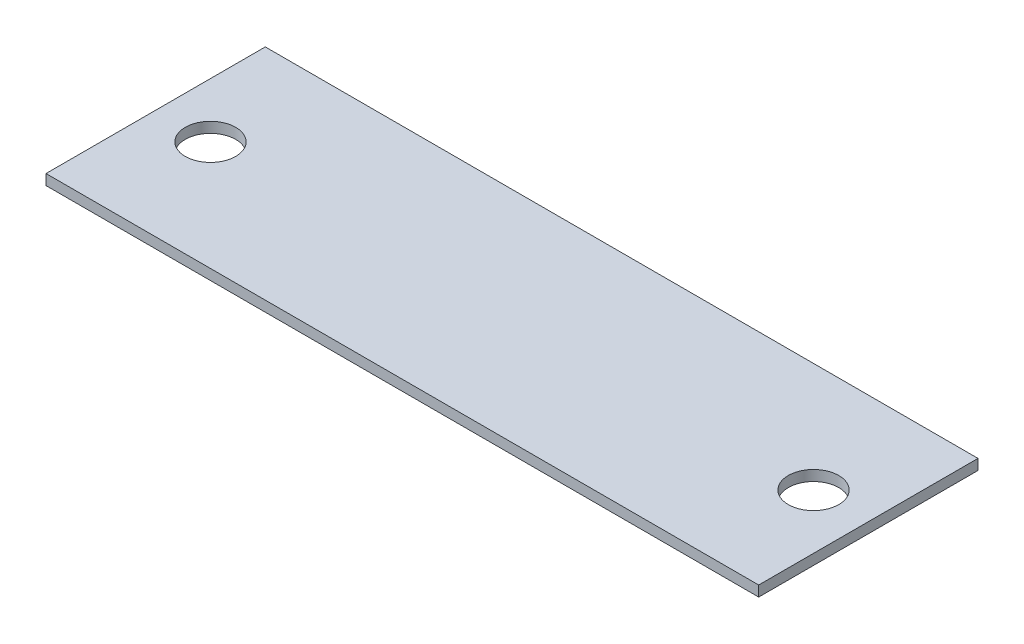
SolidWorks part; units mm, degrees
ref_plane "Front Plane" through (0, 0, 0) normal (0, 0, 1) x (1, 0, 0)
ref_plane "Top Plane" through (0, 0, 0) normal (0, 1, 0) x (1, 0, 0)
ref_plane "Right Plane" through (0, 0, 0) normal (1, 0, 0) x (0, 0, -1)
sketch "Sketch1" plane through (0, 0, 0) normal (0, 1, 0) x (1, 0, 0)
  line L0 (-34.925, 0) -> (34.925, 0) construction
  line L1 (-41.275, 12.7) -> (41.275, 12.7)
  line L2 (-41.275, 12.7) -> (-41.275, -12.7)
  line L3 (-41.275, -12.7) -> (41.275, -12.7)
  line L4 (41.275, 12.7) -> (41.275, -12.7)
  circle A0 centre (-34.925, 0) radius 2.921
  circle A1 centre (34.925, 0) radius 2.921
  point P4 (0, 12.7)
  point P5 (-41.275, 0)
  point P9 (0, 0)
  dimension "D3" = 5.842
  dimension "D1" = 82.55
  dimension "D2" = 25.4
  dimension "D4" = 6.35
extrude "Boss-Extrude1" add sketch "Sketch1" along normal blind 1.1176
sketch "Sketch4" plane through (0, 1.1176, 0) normal (0, 1, 0) x (1, 0, 0)
  line L1 (-31.5341, 11.3411) -> (-25.6159, 11.3411)
  line L2 (-31.5341, 11.3411) -> (-31.5341, 5.4229)
  line L3 (-31.5341, 5.4229) -> (-25.6159, 5.4229)
  line L4 (-25.6159, 11.3411) -> (-25.6159, 5.4229)
  point P4 (-28.575, 11.3411)
  point P5 (-31.5341, 8.382)
  dimension "D1" = 5.9182
  dimension "D2" = 5.9182
  dimension "D3" = 28.575
  dimension "D4" = 8.382
sketch "Sketch5" plane through (0, 1.1176, 0) normal (0, 1, 0) x (1, 0, 0)
  line L0 (-29.9085, 6.477) -> (30.3946, 6.477) construction
  line L2 (-29.9085, 10.287) -> (-27.2415, 10.287) construction
  line L3 (-29.9085, 10.287) -> (-29.9085, 6.477) construction
  line L4 (-29.9085, 6.477) -> (-27.2415, 6.477) construction
  line L5 (-27.2415, 10.287) -> (-27.2415, 6.477) construction
  line L6 (-26.7335, 10.287) -> (-24.0665, 10.287) construction
  line L7 (-26.7335, 10.287) -> (-26.7335, 6.477) construction
  line L8 (-26.7335, 6.477) -> (-24.0665, 6.477) construction
  line L9 (-24.0665, 10.287) -> (-24.0665, 6.477) construction
  text T0 "11U 0123456 0123456" font "Courier Std" height 3.81
  point P3 (-28.575, 10.287)
  point P4 (-29.9085, 8.382)
  point P9 (-25.4, 10.287)
  dimension "D1" = 3.81
  dimension "D2" = 2.667
  dimension "D3" = 3.175
extrude "Cut-Extrude1" [suppressed] cut sketch "Sketch5" against normal blind 0.254
pattern_linear "LPattern1" [suppressed] count 4 spacing 5.588
other "Move Face2" face at (-34.925, 1.1176, 2.921) parameters "D1"=0.0965
other "Move Face1" [suppressed] parameters "D1"=0.1176
